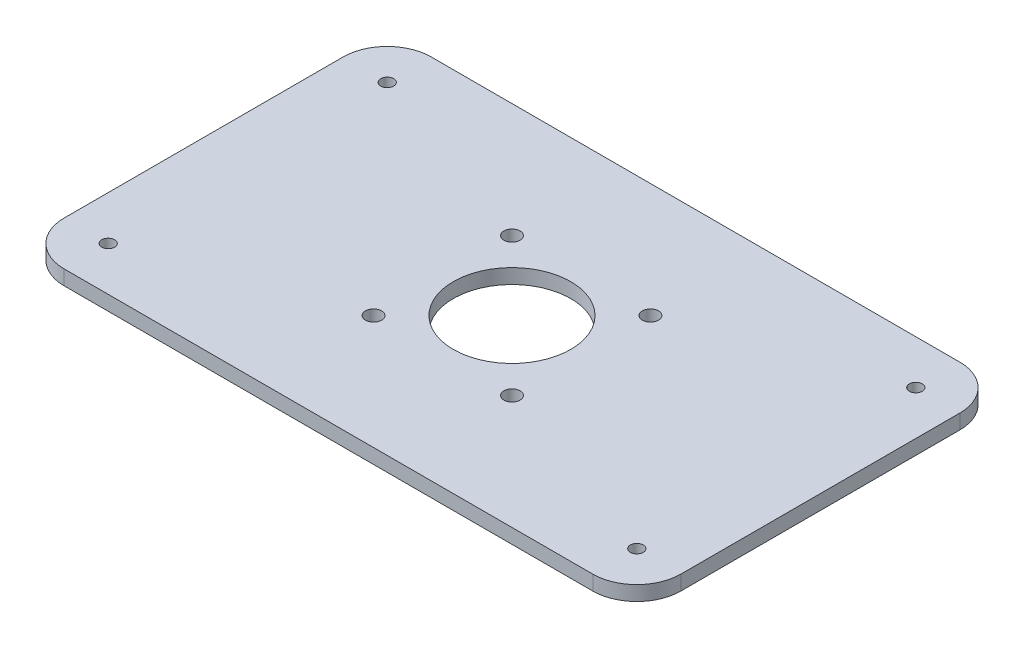
SolidWorks part; units mm, degrees
ref_plane "前视基准面" through (0, 0, 0) normal (0, 0, 1) x (1, 0, 0)
ref_plane "上视基准面" through (0, 0, 0) normal (0, 1, 0) x (1, 0, 0)
ref_plane "右视基准面" through (0, 0, 0) normal (1, 0, 0) x (0, 0, -1)
sketch "草图1" plane through (0, 0, 0) normal (0, 1, 0) x (1, 0, 0)
  circle A0 centre (0, 0) radius 20
  circle A1 centre (0, 0) radius 60
extrude "凸台-拉伸1" add sketch "草图1" along normal blind 5
sketch "草图2" plane through (0, 5, 0) normal (0, 1, 0) x (1, 0, 0)
  line L0 (-106.8682, 0) -> (92.1796, 0) construction
  line L2 (0, 64.4794) -> (0, -68.2962) construction
  circle A4 centre (-23.57, 23.57) radius 2.75
  circle A5 centre (23.57, 23.57) radius 2.75
  circle A6 centre (23.57, -23.57) radius 2.75
  circle A7 centre (-23.57, -23.57) radius 2.75
  point P16 (0, 0)
  point P17 (0, 0)
  dimension "D1" = 23.57
  dimension "D3" = 4
  dimension "D2" = 23.57
sketch "草图4" plane through (0, 0, 0) normal (0, 1, 0) x (1, 0, 0)
  line L0 (-140.1, 0) -> (119.115, 0) construction
  line L1 (-105, 62.5) -> (105, 62.5)
  line L2 (-105, 62.5) -> (-105, -62.5)
  line L3 (-105, -62.5) -> (105, -62.5)
  line L4 (105, 62.5) -> (105, -62.5)
  line L5 (0, 91.2349) -> (0, -96.2313) construction
  circle A0 centre (0, 0) radius 60
  dimension "D1" = 210
  dimension "D2" = 125
extrude "凸台-拉伸2" add sketch "草图4" along normal blind 5
sketch "草图5" plane through (0, 5, 0) normal (0, 1, 0) x (1, 0, 0)
  line L0 (105, 62.5) -> (-105, 62.5) construction
  line L1 (-105, 62.5) -> (-105, -62.5) construction
  line L2 (-153.0107, 0) -> (146.5954, 0) construction
  line L4 (0, 107.3709) -> (0, -109.3911) construction
  circle A0 centre (-90, 47.5) radius 2.2
  circle A4 centre (90, 47.5) radius 2.2
  circle A5 centre (90, -47.5) radius 2.2
  circle A6 centre (-90, -47.5) radius 2.2
  point P15 (-15, 15)
  dimension "D1" = 15
  dimension "D2" = 15
extrude "切除-拉伸2" cut sketch "草图5" against normal blind 5
fillet "圆角1" radius 15 4 edges at (-105, 2.5, 62.5) (105, 2.5, 62.5) (105, 2.5, -62.5) (-105, 2.5, -62.5)
extrude "切除-拉伸3" cut sketch "草图2" against normal blind 10
